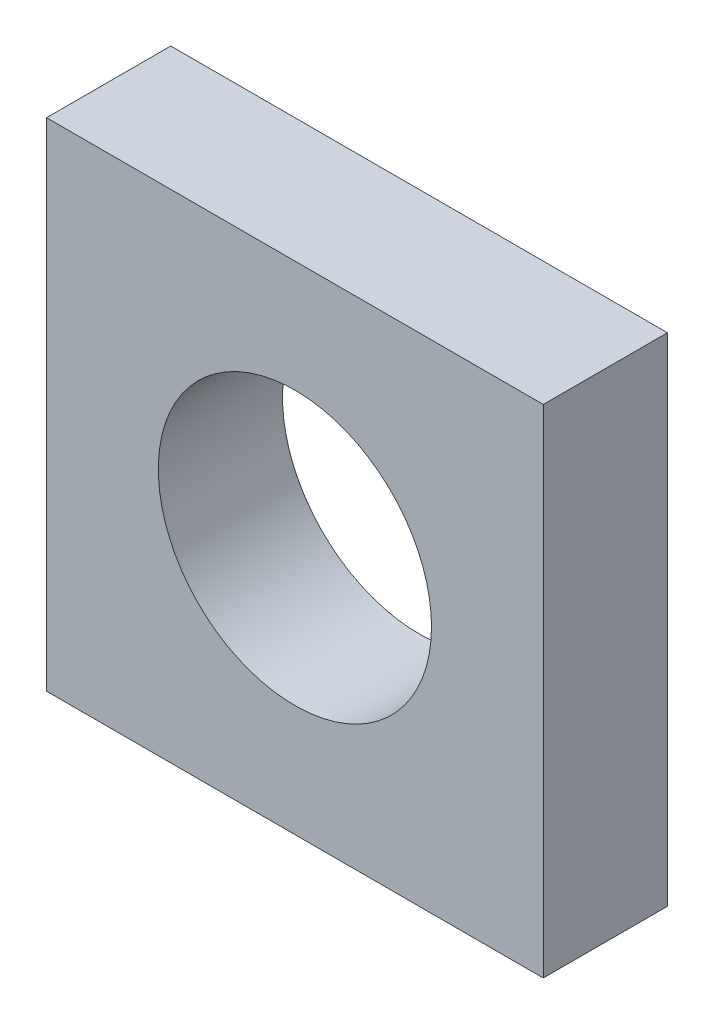
SolidWorks part; units mm, degrees
ref_plane "Front Plane" through (0, 0, 0) normal (0, 0, 1) x (1, 0, 0)
ref_plane "Top Plane" through (0, 0, 0) normal (0, 1, 0) x (1, 0, 0)
ref_plane "Right Plane" through (0, 0, 0) normal (1, 0, 0) x (0, 0, -1)
sketch "Sketch1" plane through (0, 0, 0) normal (0, 0, 1) x (1, 0, 0)
  line L1 (-20, -20) -> (20, -20)
  line L2 (-20, -20) -> (-20, 20)
  line L3 (-20, 20) -> (20, 20)
  line L4 (20, -20) -> (20, 20)
  line L5 (-20, -20) -> (20, 20) construction
  line L6 (-20, 20) -> (20, -20) construction
  circle A0 centre (0, 0) radius 11
  point P0 (0, 0)
  dimension "D3" = 22
  dimension "D1" = 40
  dimension "D2" = 40
extrude "Boss-Extrude1" add sketch "Sketch1" along normal blind 10
